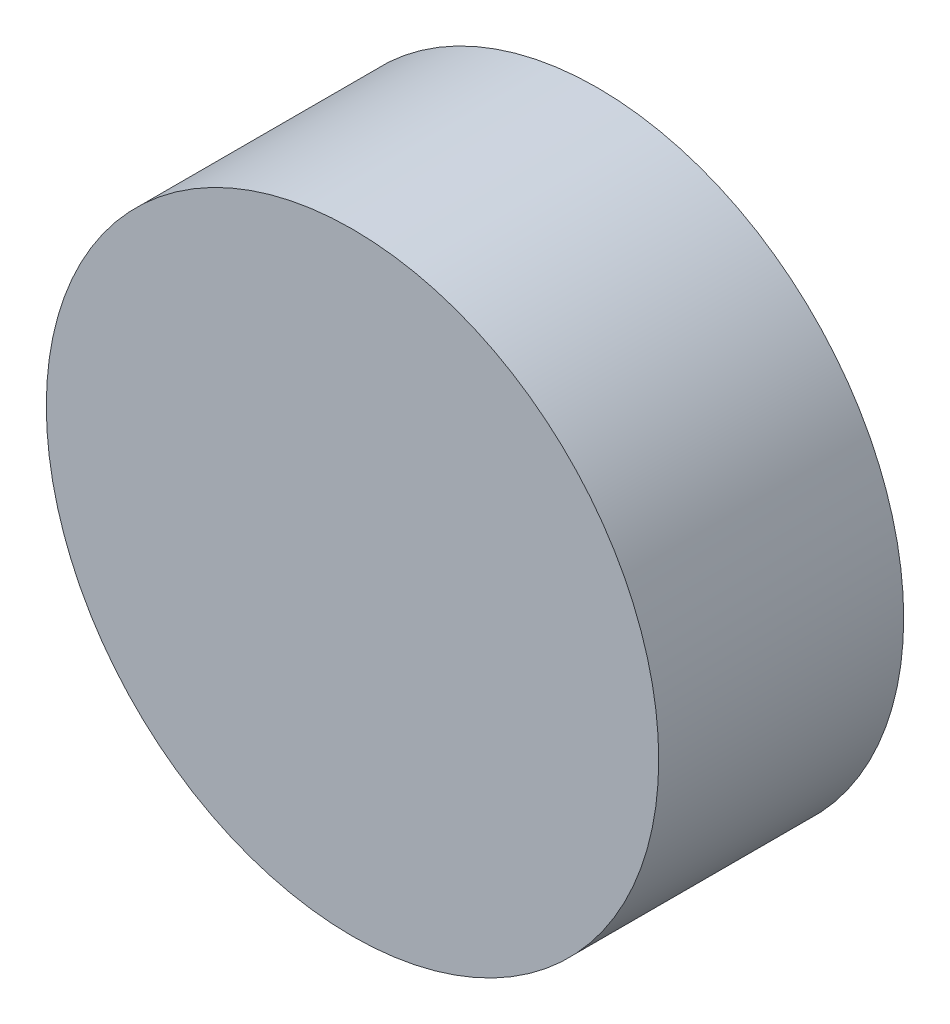
SolidWorks part; units mm, degrees
material "Neodym"
ref_plane "Ebene vorne" through (0, 0, 0) normal (1, 0, 0) x (0, 1, 0)
ref_plane "Ebene oben" through (0, 0, 0) normal (0, 0, 1) x (0, 1, 0)
ref_plane "Ebene rechts" through (0, 0, 0) normal (0, 1, 0) x (-1, 0, 0)
sketch "Skizze1" plane through (0, 0, 0) normal (0, 0, 1) x (0, 1, 0)
  circle A0 centre (0, 0) radius 2.5
extrude "Aufsatz-Linear austragen1" add sketch "Skizze1" along normal blind 2
